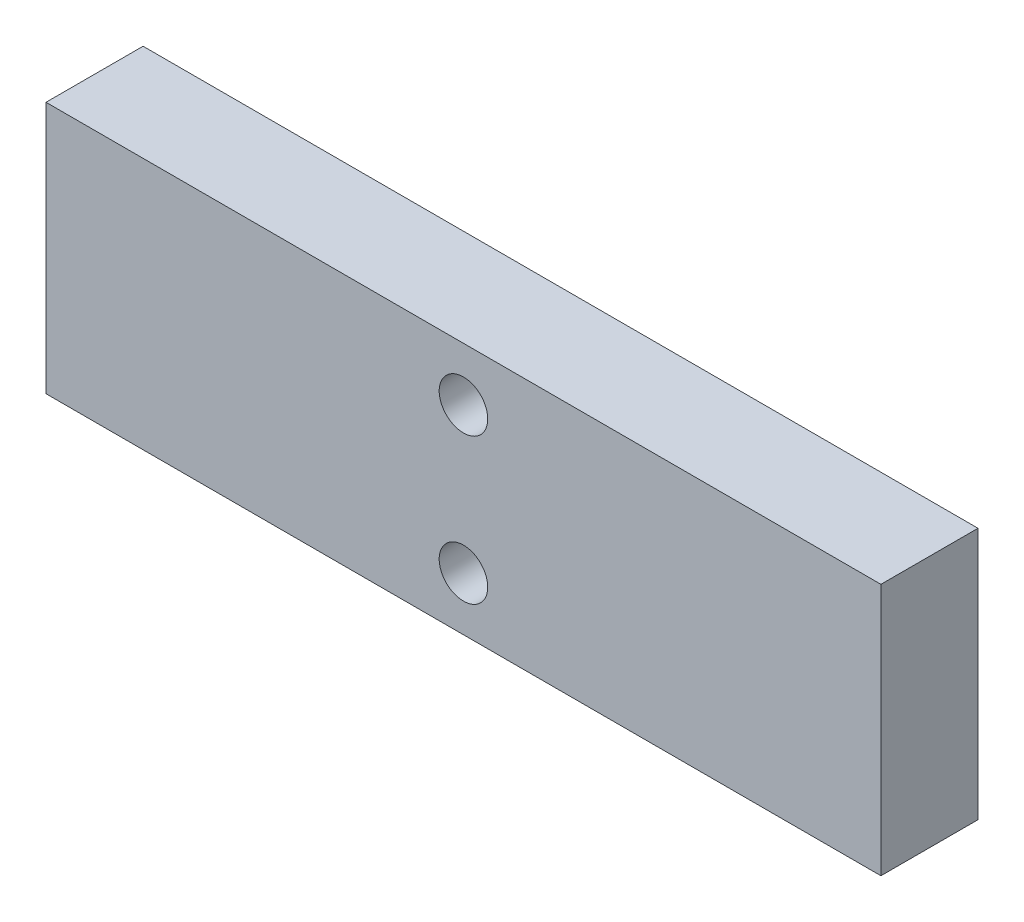
SolidWorks part; units mm, degrees
material "Plain Carbon Steel"
ref_plane "Front Plane" through (0, 0, 0) normal (0, 0, 1) x (1, 0, 0)
ref_plane "Top Plane" through (0, 0, 0) normal (0, 1, 0) x (1, 0, 0)
ref_plane "Right Plane" through (0, 0, 0) normal (1, 0, 0) x (0, 0, -1)
sketch "Sketch1" plane through (0, 0, 0) normal (0, 0, 1) x (1, 0, 0)
  line L1 (-43, -13) -> (43, -13)
  line L2 (-43, -13) -> (-43, 13)
  line L3 (-43, 13) -> (43, 13)
  line L4 (43, -13) -> (43, 13)
  line L5 (-43, -13) -> (43, 13) construction
  line L6 (-43, 13) -> (43, -13) construction
  circle A0 centre (0, 7.5) radius 2.5
  circle A1 centre (0, -7.5) radius 2.5
  point P0 (0, 0)
  dimension "D3" = 5
  dimension "D4" = 5
  dimension "D1" = 86
  dimension "D2" = 26
  dimension "D5" = 7.5
  dimension "D6" = 7.5
extrude "Boss-Extrude1" add sketch "Sketch1" along normal blind 10
